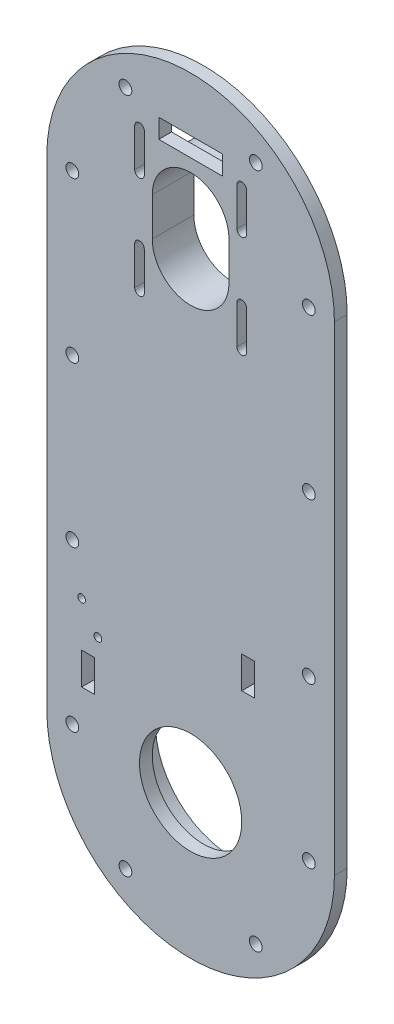
SolidWorks part; units mm, degrees
ref_plane "Plano frontal" through (0, 0, 0) normal (0, 0, 1) x (1, 0, 0)
ref_plane "Plano superior" through (0, 0, 0) normal (0, 1, 0) x (1, 0, 0)
ref_plane "Plano direito" through (0, 0, 0) normal (1, 0, 0) x (0, 0, -1)
sketch "Esboço1" plane through (0, 0, 0) normal (0, 0, 1) x (1, 0, 0)
  line L2 (45, 0) -> (45, 150)
  line L3 (-45, 150) -> (-45, 0)
  line L4 (0, 156) -> (0, 144) construction
  line L9 (0, 0) -> (0, 150) construction
  line L13 (12, 156) -> (12, 144)
  line L16 (-12, 156) -> (-12, 144)
  line L19 (15.99, 159.99) -> (15.99, 171.99) construction
  line L22 (15.99, 134.01) -> (-15.99, 134.01) construction
  line L27 (15.99, 134.01) -> (15.99, 165.99) construction
  line L28 (15.99, 165.99) -> (-15.99, 165.99) construction
  line L29 (-15.99, 134.01) -> (-15.99, 165.99) construction
  line L30 (15.99, 134.01) -> (-15.99, 165.99) construction
  line L31 (15.99, 165.99) -> (-15.99, 134.01) construction
  line L32 (14.49, 159.99) -> (14.49, 171.99)
  line L33 (17.49, 159.99) -> (17.49, 171.99)
  line L34 (-15.99, 159.99) -> (-15.99, 171.99) construction
  line L35 (-17.49, 159.99) -> (-17.49, 171.99)
  line L36 (-14.49, 159.99) -> (-14.49, 171.99)
  line L37 (15.99, 128.01) -> (15.99, 140.01) construction
  line L38 (14.49, 128.01) -> (14.49, 140.01)
  line L39 (17.49, 128.01) -> (17.49, 140.01)
  line L40 (-15.99, 128.01) -> (-15.99, 140.01) construction
  line L41 (-17.49, 128.01) -> (-17.49, 140.01)
  line L42 (-14.49, 128.01) -> (-14.49, 140.01)
  arc A8 (-45, 0) -> (45, 0) centre (0, 0) ccw
  arc A9 (45, 150) -> (-45, 150) centre (0, 150) ccw
  circle A10 centre (0, 0) radius 16
  arc A26 (12, 156) -> (-12, 156) centre (0, 156) ccw
  arc A29 (-12, 144) -> (12, 144) centre (0, 144) ccw
  arc A30 (14.49, 159.99) -> (17.49, 159.99) centre (15.99, 159.99) ccw
  arc A31 (17.49, 171.99) -> (14.49, 171.99) centre (15.99, 171.99) ccw
  arc A32 (-17.49, 159.99) -> (-14.49, 159.99) centre (-15.99, 159.99) ccw
  arc A33 (-14.49, 171.99) -> (-17.49, 171.99) centre (-15.99, 171.99) ccw
  arc A34 (14.49, 128.01) -> (17.49, 128.01) centre (15.99, 128.01) ccw
  arc A35 (17.49, 140.01) -> (14.49, 140.01) centre (15.99, 140.01) ccw
  arc A36 (-17.49, 128.01) -> (-14.49, 128.01) centre (-15.99, 128.01) ccw
  arc A37 (-14.49, 140.01) -> (-17.49, 140.01) centre (-15.99, 140.01) ccw
  point P4 (0, 150)
  point P18 (0, 150)
  point P22 (15.99, 165.99)
  point P31 (-15.99, 165.99)
  point P39 (15.99, 134.01)
  point P46 (-15.99, 134.01)
  point P52 (-15.99, 134.01)
  dimension "D1" = 90
  dimension "D2" = 150
  dimension "D3" = 32
  dimension "D4" = 12
  dimension "D6" = 31.98
  dimension "D7" = 31.98
  dimension "D10" = 2
  dimension "D11" = 150
  dimension "D5" = 12
  dimension "D8" = 1.5
  dimension "D9" = 12
  dimension "D12" = 2
extrude "Ressalto-extrusão1" add sketch "Esboço1" along normal blind 4
sketch "Esboço2" plane through (0, 0, 0) normal (0, 0, 1) x (1, 0, 0)
  circle A0 centre (0, 0) radius 24
  circle A1 centre (0, 0) radius 27
  dimension "D1" = 48
  dimension "D2" = 54
extrude "Ressalto-extrusão2" add sketch "Esboço2" against normal blind 9
sketch "Esboço4" plane through (0, 0, 4) normal (0, 0, 1) x (1, 0, 0)
  line L0 (37, 150) -> (37, 0) construction
  line L1 (-37, 150) -> (-37, 0) construction
  line L2 (-37, 75) -> (37, 75) construction
  line L3 (0, 75) -> (0, 150) construction
  arc A0 (-37, 0) -> (37, 0) centre (0, 0) ccw construction
  arc A1 (37, 150) -> (-37, 150) centre (0, 150) ccw construction
  circle A2 centre (-37, 150) radius 2
  circle A3 centre (-37, 100) radius 2
  circle A4 centre (-37, 50) radius 2
  circle A5 centre (-37, 0) radius 2
  circle A6 centre (-20.3971, 180.87) radius 2
  circle A7 centre (-20.3971, -30.87) radius 2
  circle A8 centre (20.3971, -30.87) radius 2
  circle A9 centre (20.3971, 180.87) radius 2
  circle A10 centre (37, 0) radius 2
  circle A11 centre (37, 50) radius 2
  circle A12 centre (37, 100) radius 2
  circle A13 centre (37, 150) radius 2
  dimension "D1" = 74
  dimension "D2" = 4
  dimension "D4" = 30.87
  dimension "D3" = 4
extrude "Corte-extrusão1" cut sketch "Esboço4" against normal up to surface (4 mm away) up to face at (27, 0, 0)
sketch "Esboço6" plane through (0, 0, 0) normal (0, 0, -1) x (-1, 0, 0)
  line L0 (-12, 150) -> (12, 150) construction
  line L1 (-12, 144) -> (-12, 156) construction
  line L2 (12, 156) -> (12, 144) construction
  line L3 (0, 168) -> (0, 150) construction
  line L4 (0, 150) -> (0, 132) construction
  line L5 (0, 144) -> (0, 156) construction
  line L6 (-12, 144) -> (-12, 156)
  line L7 (12, 144) -> (12, 156)
  line L8 (0, 143) -> (0, 157) construction
  line L9 (-14, 143) -> (-14, 157)
  line L10 (14, 143) -> (14, 157)
  arc A2 (12, 156) -> (-12, 156) centre (0, 156) ccw construction
  arc A3 (-12, 144) -> (12, 144) centre (0, 144) ccw construction
  arc A4 (-12, 144) -> (12, 144) centre (0, 144) ccw
  arc A5 (12, 156) -> (-12, 156) centre (0, 156) ccw
  arc A6 (-14, 143) -> (14, 143) centre (0, 143) ccw
  arc A7 (14, 157) -> (-14, 157) centre (0, 157) ccw
  point P3 (0, 150)
  point P11 (0, 150)
  point P26 (0, 150)
  dimension "D1" = 12
  dimension "D2" = 12
  dimension "D3" = 14
  dimension "D4" = 14
extrude "Ressalto-extrusão3" add sketch "Esboço6" along normal blind 9
sketch "Esboço8" plane through (0, 0, -9) normal (0, 0, -1) x (-1, 0, 0)
  line L0 (0, 129) -> (0, 27)
  arc A0 (-14, 143) -> (14, 143) centre (0, 143) ccw construction
  circle A1 centre (0, 0) radius 27 construction
  circle A2 centre (0, 0) radius 27 construction
rib "Nervura4" sketch "Esboço8" sketch "Esboço8" thickness 5 extrusion direction normal to sketch draft on no parameters "D1"=5
sketch "Esboço9" plane through (0, 0, 0) normal (0, 0, -1) x (-1, 0, 0)
  line L0 (0, 0) -> (45, 46.9042) construction
  line L1 (45, 150) -> (45, 0) construction
  line L2 (0, 0) -> (45, 42.6497) construction
  line L3 (-45, 0) -> (-45, 150) construction
  line L4 (34.1051, 11.516) -> (30.1051, 11.516)
  line L5 (34.1051, 11.516) -> (34.1051, 21.516)
  line L6 (34.1051, 21.516) -> (30.1051, 21.516)
  line L7 (30.1051, 11.516) -> (30.1051, 21.516)
  line L8 (-10.0344, 178) -> (9.9656, 178)
  line L9 (-10.0344, 178) -> (-10.0344, 172)
  line L10 (-10.0344, 172) -> (9.9656, 172)
  line L11 (9.9656, 178) -> (9.9656, 172)
  line L12 (-10.0344, 178) -> (9.9656, 172) construction
  line L13 (-10.0344, 172) -> (9.9656, 178) construction
  line L14 (-16, 35.5482) -> (-20, 35.5482)
  line L15 (-16, 35.5482) -> (-16, 45.5482)
  line L16 (-16, 45.5482) -> (-20, 45.5482)
  line L17 (-20, 35.5482) -> (-20, 45.5482)
  circle A0 centre (29.0323, 27.516) radius 1.2
  circle A1 centre (34.1051, 35.5482) radius 1.2
  point P14 (-0.0344, 175)
  point P15 (32.1051, 21.516)
  point P24 (-18, 35.5482)
  dimension "D3" = 2.4
  dimension "D4" = 9.5
  dimension "D5" = 40
  dimension "D1" = 62
  dimension "D2" = 65
  dimension "D6" = 4
  dimension "D7" = 10
  dimension "D8" = 20
  dimension "6" = 6
  dimension "D9" = 6
  dimension "D10" = 175
  dimension "D11" = 10
  dimension "D12" = 4
  dimension "D13" = 25
extrude "Corte-extrusão2" cut sketch "Esboço9" against normal up to surface (4 mm away) up to face at (0, 150, 4)
